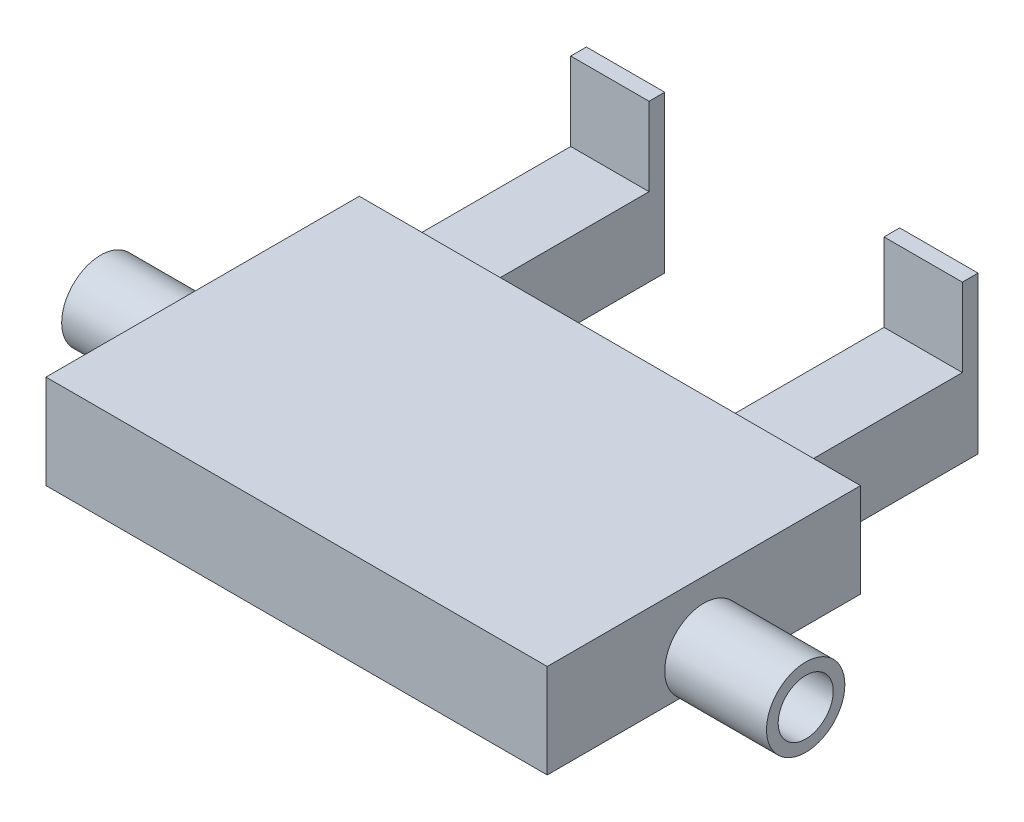
SolidWorks part; units mm, degrees
ref_plane "Front Plane" through (0, 0, 0) normal (0, 0, 1) x (1, 0, 0)
ref_plane "Top Plane" through (0, 0, 0) normal (0, 1, 0) x (1, 0, 0)
ref_plane "Right Plane" through (0, 0, 0) normal (1, 0, 0) x (0, 0, -1)
sketch "Sketch1" plane through (0, 0, 0) normal (0, 1, 0) x (1, 0, 0)
  line L1 (-32, 20) -> (32, 20)
  line L2 (-32, 20) -> (-32, -20)
  line L3 (-32, -20) -> (32, -20)
  line L4 (32, 20) -> (32, -20)
  line L5 (-32, 20) -> (32, -20) construction
  line L6 (-32, -20) -> (32, 20) construction
  point P0 (0, 0)
  dimension "D1" = 64
  dimension "D2" = 40
extrude "Boss-Extrude1" add sketch "Sketch1" along normal blind 12
sketch "Sketch2" plane through (32, 0, 0) normal (1, 0, 0) x (0, 0, -1)
  line L0 (-20, 12) -> (20, 12) construction
  line L3 (-20, 12) -> (-20, 0) construction
  circle A0 centre (0, 4) radius 5
  circle A1 centre (0, 4) radius 3.515
  dimension "D1" = 10
  dimension "D4" = 7.03
  dimension "D2" = 8
  dimension "D3" = 20
extrude "Boss-Extrude2" add sketch "Sketch2" along normal blind 13
sketch "Sketch3" plane through (-32, 0, 0) normal (-1, 0, 0) x (0, 0, 1)
  line L0 (-20, 12) -> (-20, 0) construction
  line L1 (-20, 12) -> (20, 12) construction
  circle A0 centre (0, 4) radius 5
  circle A1 centre (0, 4) radius 3.515
  dimension "D1" = 10
  dimension "D4" = 7.03
  dimension "D2" = 8
  dimension "D3" = 20
extrude "Boss-Extrude3" add sketch "Sketch3" along normal blind 13
sketch "Sketch5" plane through (0, 0, -20) normal (0, 0, -1) x (-1, 0, 0)
  line L1 (-25, 11) -> (-15, 11)
  line L2 (-25, 11) -> (-25, 1)
  line L3 (-25, 1) -> (-15, 1)
  line L4 (-15, 11) -> (-15, 1)
  line L5 (-25, 11) -> (-15, 1) construction
  line L6 (-25, 1) -> (-15, 11) construction
  line L7 (15, 11) -> (25, 11)
  line L8 (15, 11) -> (15, 1)
  line L9 (15, 1) -> (25, 1)
  line L10 (25, 11) -> (25, 1)
  line L11 (15, 11) -> (25, 1) construction
  line L12 (15, 1) -> (25, 11) construction
  line L14 (-32, 12) -> (32, 12) construction
  point P0 (-20, 6)
  point P5 (20, 6)
  dimension "D1" = 10
  dimension "D2" = 10
  dimension "D3" = 1
  dimension "D4" = 20
  dimension "D5" = 10
  dimension "D6" = 10
  dimension "D7" = 1
  dimension "D8" = 20
extrude "Boss-Extrude4" add sketch "Sketch5" along normal blind 22
sketch "Sketch6" plane through (0, 11, 0) normal (0, 1, 0) x (1, 0, 0)
  line L0 (15, 42) -> (25, 42)
  line L1 (15, 42) -> (25, 42) construction
  line L2 (15, 42) -> (15, 20) construction
  line L3 (25, 42) -> (25, 40)
  line L4 (25, 42) -> (25, 20) construction
  line L5 (25, 40) -> (15, 40)
  line L6 (15, 40) -> (15, 42)
  line L7 (-15, 42) -> (-25, 42)
  line L8 (-25, 42) -> (-25, 40)
  line L9 (-25, 42) -> (-25, 20) construction
  line L10 (-25, 40) -> (-15, 40)
  line L11 (-15, 42) -> (-15, 20) construction
  line L12 (-15, 40) -> (-15, 42)
  dimension "D1" = 10
  dimension "D2" = 10
  dimension "D3" = 2
  dimension "D4" = 2
extrude "Boss-Extrude5" add sketch "Sketch6" along normal blind 10
